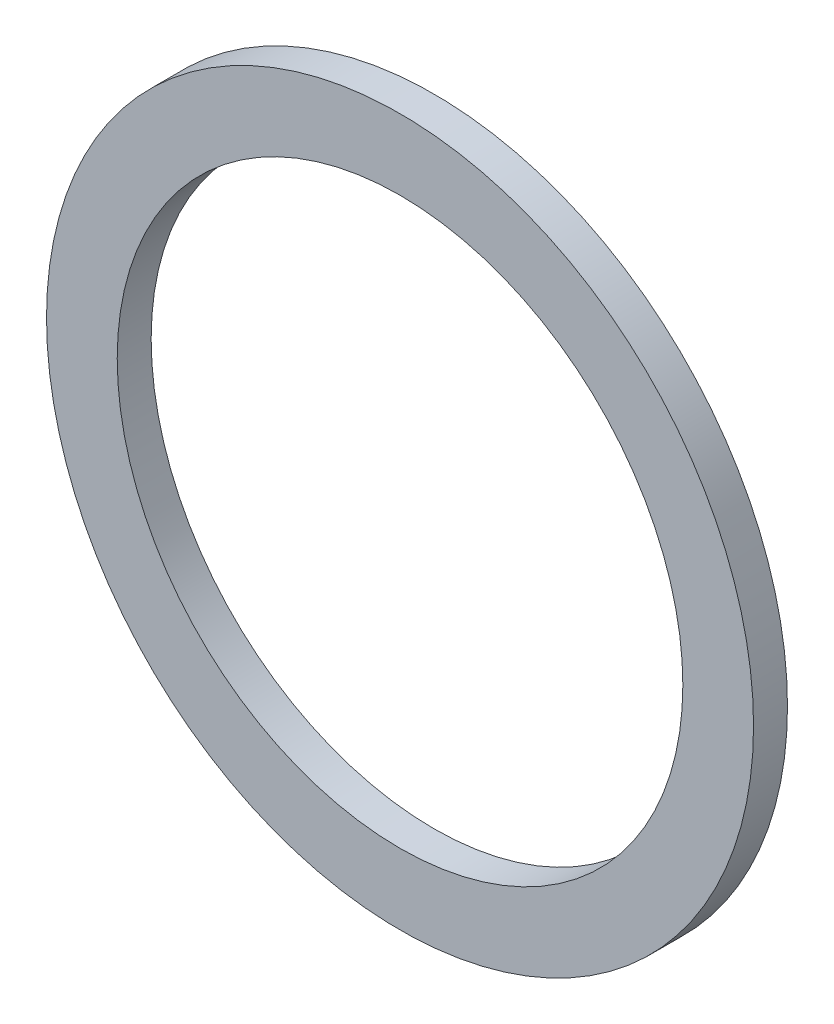
SolidWorks part; units mm, degrees
ref_plane "Спереди" through (0, 0, 0) normal (0, 0, 1) x (1, 0, 0)
ref_plane "Сверху" through (0, 0, 0) normal (0, 1, 0) x (1, 0, 0)
ref_plane "Справа" through (0, 0, 0) normal (1, 0, 0) x (0, 0, -1)
sketch "Эскиз1" plane through (0, 0, 0) normal (0, 0, 1) x (1, 0, 0)
  circle A0 centre (0, 0) radius 12.5
  circle A1 centre (0, 0) radius 10
  dimension "D1" = 2.5
  dimension "D2" = 20
extrude "Вытянуть1" add sketch "Эскиз1" along normal blind 1.2
